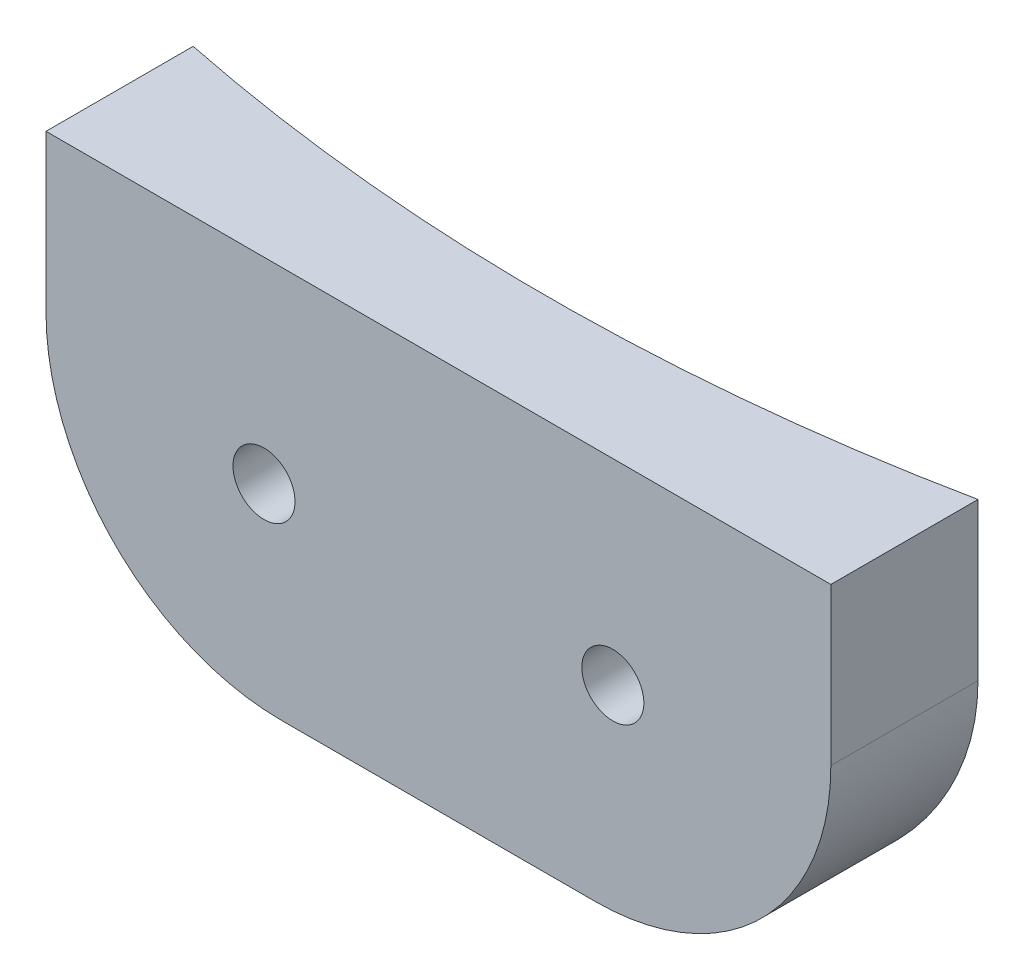
SolidWorks part; units mm, degrees
material "6061 Alloy"
ref_plane "Front Plane" through (0, 0, 0) normal (0, 0, 1) x (1, 0, 0)
ref_plane "Top Plane" through (0, 0, 0) normal (0, 1, 0) x (1, 0, 0)
ref_plane "Right Plane" through (0, 0, 0) normal (1, 0, 0) x (0, 0, -1)
sketch "Sketch1" plane through (0, 0, 0) normal (0, 1, 0) x (1, 0, 0)
  line L0 (-12.7, -62.217) -> (-12.7, -65.4543)
  line L1 (12.7, -62.217) -> (12.7, -65.4543)
  line L2 (-12.7, -66.9795) -> (12.7, -66.9795)
  line L3 (-12.7, -65.4543) -> (-12.7, -66.9795)
  line L4 (12.7, -65.4543) -> (12.7, -66.9795)
  circle A0 centre (0, 0) radius 63.5
  circle A1 centre (0, 0) radius 66.675
  dimension "D1" = 127
  dimension "D3" = 12.7
  dimension "D4" = 12.7
  dimension "D5" = 4.7625
  dimension "D2" = 3.175
extrude "Boss-Extrude1" add sketch "Sketch1" along normal blind 12.7 contours L0 A1 L1 A0 | A1 L3 L2 | A1 L2 L4
sketch "Sketch2" plane through (0, 0, 0) normal (0, 0, 1) x (1, 0, 0)
  line L0 (0, 12.7) -> (0, 0) construction
  line L5 (-12.7, 0) -> (12.7, 0)
  line L6 (12.7, 0) -> (12.7, 12.7)
  line L7 (12.7, 12.7) -> (-12.7, 12.7)
  line L12 (-12.7, 12.7) -> (-12.7, 0)
  line L13 (-12.7, 0) -> (12.7, 0)
  line L14 (12.7, 0) -> (12.7, 12.7)
  line L15 (12.7, 12.7) -> (-12.7, 12.7)
  line L16 (-12.7, 12.7) -> (-12.7, 0)
  circle A0 centre (-5.6444, 6.35) radius 1.0033
  dimension "D6" = 2.0066
  dimension "D5" = 5.6444
  dimension "D2" = 6.35
  dimension "D1" = 0
extrude "Cut-Extrude1" cut sketch "Sketch2" along normal up to surface (66.9795 mm away) contours A0 up to face at (0, 6.35, 66.9795)
mirror "Mirror1" about plane through (0, 0, 0) normal (1, 0, 0) of "Cut-Extrude1"
fillet "Fillet1" radius 7.62 2 edges at (-12.7, 0, 64.5983) (12.7, 0, 64.5983)
equation "\"Middle Coupler Inner Daimeter\"= 4.5in"
equation "\"Middle Coupler  Wall Thickness\" = 0.25in"
equation "\"Middle Coupler Bottom Thickness\"= 0.2in"
equation "\"Bearing Rail Offset\"= 0.45in"
equation "\"3-56 UNF Tap\"= 0.089in"
equation "\"3-56 UNF Clearance\"= 0.104in"
equation "\"Ball Bearing Distance\"= 0.03in"
equation "\"TCA Outer Diameter\" = 6.625in"
equation "\"D1@Sketch1\"=\"Middle Coupler Inner Daimeter\"+0.5"
equation "\"D2@Sketch1\"=1/8"
equation "\"D3@Sketch1\"=0.5"
equation "\"D4@Sketch1\"=\"D3@Sketch1\""
equation "\"D6@Sketch2\"=\"3-48 Tap\""
equation "\"Interstage Aeroframe Wall Thickness\" = 0.072in"
equation "\"Compression Spring OD\"= 0.42in"
equation "\"10-24 Tap\"= 0.157in"
equation "\"10-24 Clearance\"= 0.196in"
equation "\"Lower Stage Fuselage Wall Thickness\" = 0.25in"
equation "\"6-32 Tap\" = 0.107in"
equation "\"1/4-20 Tap\" = 0.201in"
equation "\"3-48 Tap\"= 0.079in"
equation "\"3-48 Clearance\" = 0.104in"
equation "\"6-32 Clearance\" = 0.144"
equation "\"12-24 Tap\" = 0.177in"
equation "\"D5@Sketch1\"=3/16"
